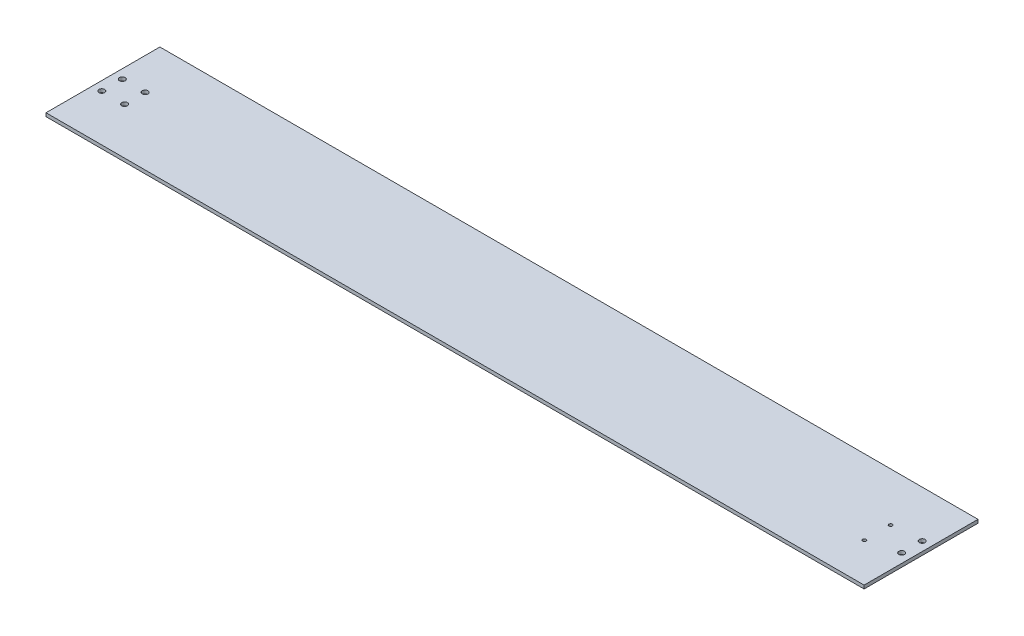
SolidWorks part; units mm, degrees
ref_plane "Front Plane" through (0, 0, 0) normal (0, 0, 1) x (1, 0, 0)
ref_plane "Top Plane" through (0, 0, 0) normal (0, 1, 0) x (1, 0, 0)
ref_plane "Right Plane" through (0, 0, 0) normal (1, 0, 0) x (0, 0, -1)
sketch "Sketch1" plane through (0, 0, 0) normal (0, 1, 0) x (1, 0, 0)
  line L1 (0, 0) -> (-718.32, 0)
  line L2 (0, 0) -> (0, 100)
  line L3 (0, 100) -> (-718.32, 100)
  line L4 (-718.32, 0) -> (-718.32, 100)
  dimension "D1" = 718.32
  dimension "D2" = 100
extrude "Boss-Extrude1" add sketch "Sketch1" along normal blind 3
sketch "Sketch2" plane through (0, 3, 0) normal (0, 1, 0) x (1, 0, 0)
  line L0 (-718.32, 100) -> (-718.32, 0) construction
  line L2 (0, 100) -> (-718.32, 100) construction
  line L3 (-718.32, 0) -> (0, 0) construction
  circle A0 centre (-710.32, 59) radius 2.5
  circle A1 centre (-8, 59) radius 2.5
  circle A2 centre (-8, 41) radius 2.5
  circle A3 centre (-710.32, 41) radius 2.5
  dimension "D3" = 5
  dimension "D4" = 5
  dimension "D5" = 5
  dimension "D6" = 5
  dimension "D7" = 18
  dimension "D1" = 702.32
  dimension "D2" = 8
  dimension "D8" = 41
  dimension "D9" = 0
  dimension "D10" = 0
  dimension "D11" = 18
  dimension "D12" = 41
extrude "Cut-Extrude1" cut sketch "Sketch2" against normal blind 30
sketch "Sketch3" plane through (0, 3, 0) normal (0, 1, 0) x (1, 0, 0)
  line L0 (-718.32, 0) -> (0, 0) construction
  circle A0 centre (-690.32, 59) radius 2.5
  circle A1 centre (-690.32, 41) radius 2.5
  circle A3 centre (-710.32, 41) radius 2.5 construction
  dimension "D3" = 5
  dimension "D4" = 5
  dimension "D2" = 20
  dimension "D5" = 18
  dimension "D6" = 41
extrude "Cut-Extrude2" cut sketch "Sketch3" against normal blind 30
sketch "Sketch4" plane through (0, 3, 0) normal (0, 1, 0) x (1, 0, 0)
  line L0 (0, 0) -> (0, 100) construction
  line L1 (-718.32, 0) -> (0, 0) construction
  circle A0 centre (-34, 57.2768) radius 1.5
  circle A1 centre (-34, 34.2768) radius 1.5
  dimension "D1" = 3
  dimension "D2" = 3
  dimension "D3" = 23
  dimension "D4" = 0
  dimension "D5" = 34
  dimension "D6" = 34.2768
extrude "Cut-Extrude3" cut sketch "Sketch4" against normal blind 10
